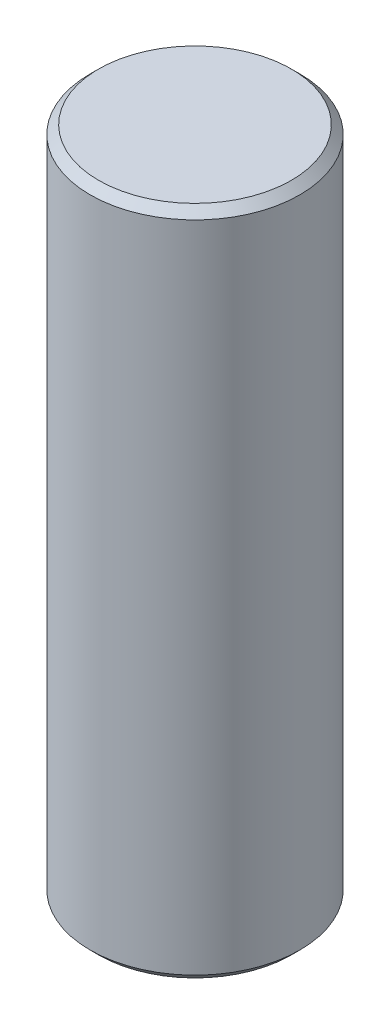
SolidWorks part; units mm, degrees
ref_plane "Front Plane" through (0, 0, 0) normal (0, 0, 1) x (1, 0, 0)
ref_plane "Top Plane" through (0, 0, 0) normal (0, 1, 0) x (1, 0, 0)
ref_plane "Right Plane" through (0, 0, 0) normal (1, 0, 0) x (0, 0, -1)
sketch "Sketch1" plane through (0, 0, 0) normal (0, 1, 0) x (1, 0, 0)
  circle A0 centre (0, 0) radius 2.5
extrude "Boss-Extrude1" add sketch "Sketch1" along normal mid plane 16
chamfer "Chamfer1" distance 0.2 angle 45 2 edges at (0, -8, 2.5) (0, 8, 2.5)
